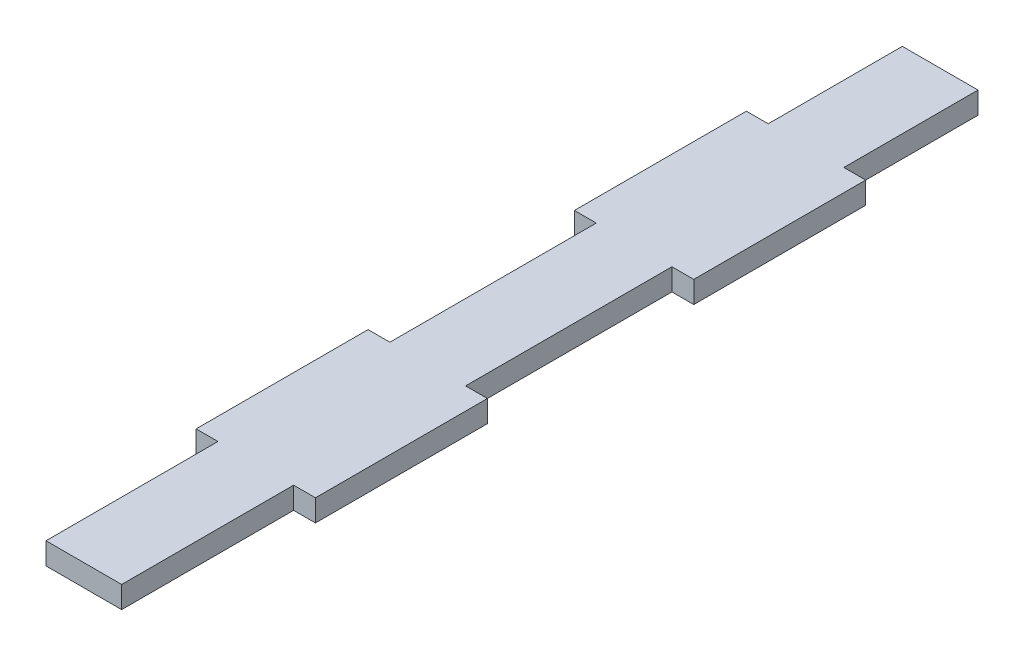
SolidWorks part; units mm, degrees
material "Acrylic (Medium-high impact)"
ref_plane "Front Plane" through (0, 0, 0) normal (0, 0, 1) x (1, 0, 0)
ref_plane "Top Plane" through (0, 0, 0) normal (0, 1, 0) x (1, 0, 0)
ref_plane "Right Plane" through (0, 0, 0) normal (1, 0, 0) x (0, 0, -1)
sketch "Sketch1" plane through (0, 0, 0) normal (0, 1, 0) x (1, 0, 0)
  line L1 (0, 0) -> (22, 0)
  line L2 (0, 0) -> (0, 50)
  line L3 (0, 249) -> (22, 249)
  line L4 (22, 0) -> (22, 50)
  line L5 (0, 50) -> (-6.35, 50)
  line L7 (0, 100) -> (-6.35, 100)
  line L8 (-6.35, 50) -> (-6.35, 100)
  line L9 (0, 160) -> (-6.35, 160)
  line L10 (-6.35, 160) -> (-6.35, 210)
  line L11 (0, 210) -> (-6.35, 210)
  line L13 (22, 50) -> (28.35, 50)
  line L15 (22, 100) -> (28.35, 100)
  line L16 (28.35, 50) -> (28.35, 100)
  line L17 (22, 160) -> (28.35, 160)
  line L18 (28.35, 160) -> (28.35, 210)
  line L19 (22, 210) -> (28.35, 210)
  line L20 (0, 100) -> (0, 160)
  line L21 (22, 100) -> (22, 160)
  line L22 (22, 210) -> (22, 249)
  line L23 (0, 210) -> (0, 249)
  dimension "D1" = 249
  dimension "D2" = 22
  dimension "D3" = 6.35
  dimension "D4" = 50
  dimension "D5" = 50
  dimension "D7" = 6.35
  dimension "D8" = 50
  dimension "D9" = 50
  dimension "D11" = 39
  dimension "D12" = 39
  dimension "D6" = 2
  dimension "D10" = 2
extrude "Boss-Extrude1" add sketch "Sketch1" along normal blind 6.35
